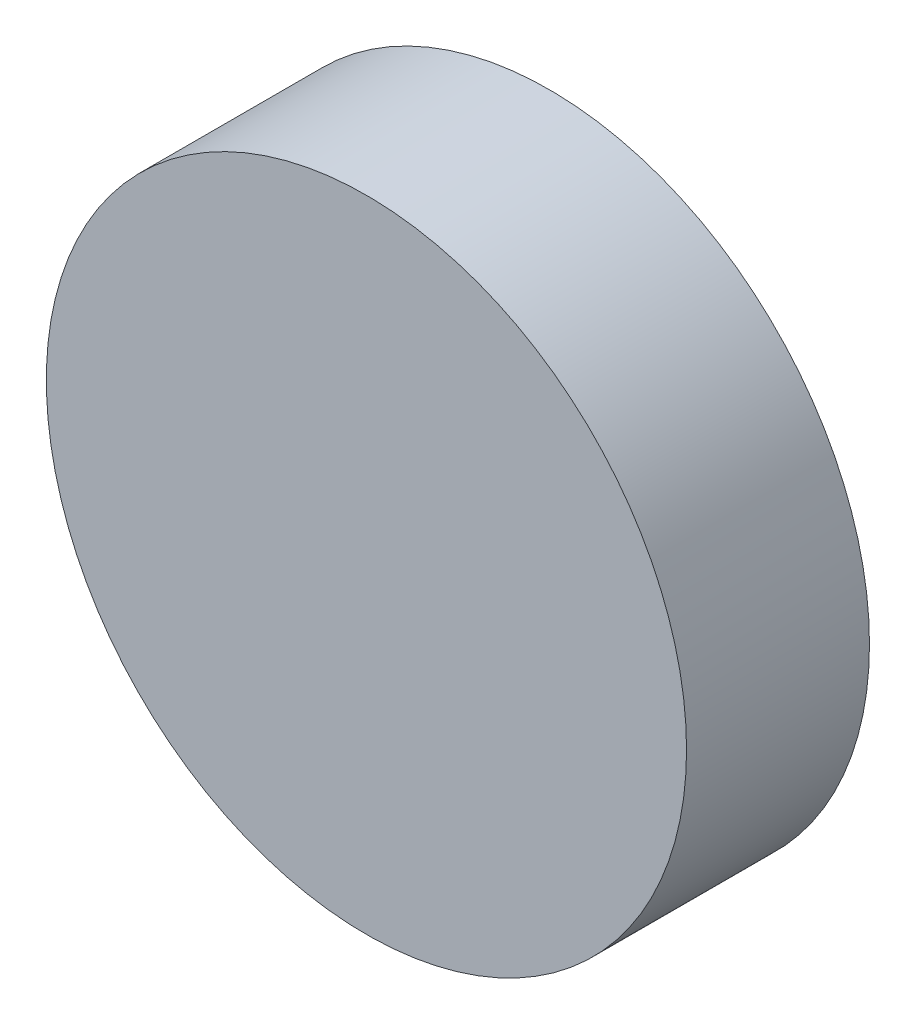
SolidWorks part; units mm, degrees
ref_plane "Front Plane" through (0, 0, 0) normal (0, 0, 1) x (1, 0, 0)
ref_plane "Top Plane" through (0, 0, 0) normal (0, 1, 0) x (1, 0, 0)
ref_plane "Right Plane" through (0, 0, 0) normal (1, 0, 0) x (0, 0, -1)
sketch "Sketch1" plane through (0, 0, 0) normal (0, 0, 1) x (1, 0, 0)
  circle A0 centre (0, 0) radius 17.5
  dimension "D1" = 35
extrude "Boss-Extrude1" add sketch "Sketch1" along normal blind 10
sketch "Sketch2" plane through (0, 0, 10) normal (0, 0, 1) x (1, 0, 0)
